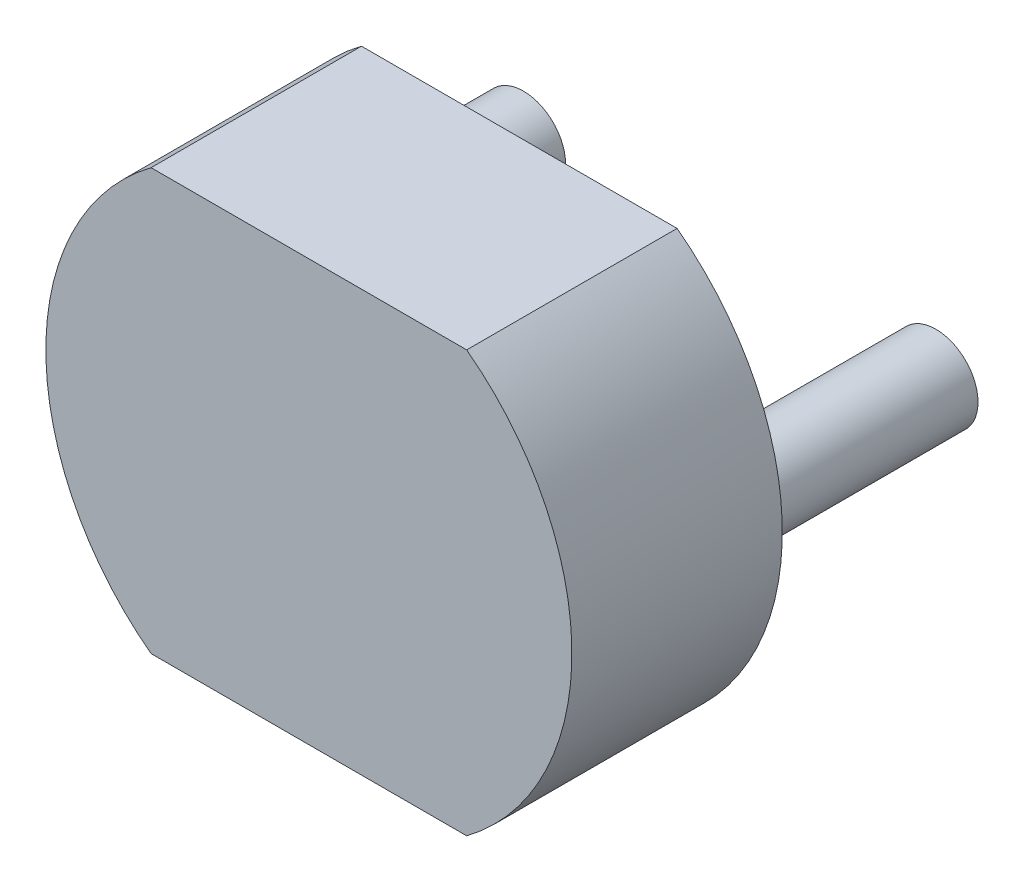
SolidWorks part; units mm, degrees
material "Никель"
ref_plane "Спереди" through (0, 0, 0) normal (0, 0, 1) x (1, 0, 0)
ref_plane "Сверху" through (0, 0, 0) normal (0, 1, 0) x (1, 0, 0)
ref_plane "Справа" through (0, 0, 0) normal (1, 0, 0) x (0, 0, -1)
sketch "Эскиз1" plane through (0, 0, 0) normal (0, 0, 1) x (1, 0, 0)
  line L1 (-1.5, -2) -> (1.5, -2)
  line L2 (-1.5, -2) -> (-1.5, 2)
  line L3 (-1.5, 2) -> (1.5, 2)
  line L4 (1.5, -2) -> (1.5, 2)
  line L5 (-1.5, -2) -> (1.5, 2) construction
  line L6 (-1.5, 2) -> (1.5, -2) construction
  circle A0 centre (0, 0) radius 2.5
  dimension "D1" = 5
  dimension "D2" = 4
extrude "Бобышка-Вытянуть1" add sketch "Эскиз1" along normal blind 2 contours L2 A0 | L1 L4 L3 L2 | L4 A0
sketch "Эскиз2" plane through (0, 0, 0) normal (0, 0, -1) x (-1, 0, 0)
  line L0 (-1000, 0) -> (49000, 0) construction
  line L1 (0, -1000) -> (0, 49000) construction
  circle A0 centre (-1.96, 0) radius 0.4
  arc A1 (-1.5, 2) -> (-1.5, -2) centre (0, 0) ccw construction
  circle A2 centre (1.96, 0) radius 0.4
  dimension "D1" = 0.8
  dimension "D2" = 1.96
extrude "Бобышка-Вытянуть2" add sketch "Эскиз2" along normal blind 2
